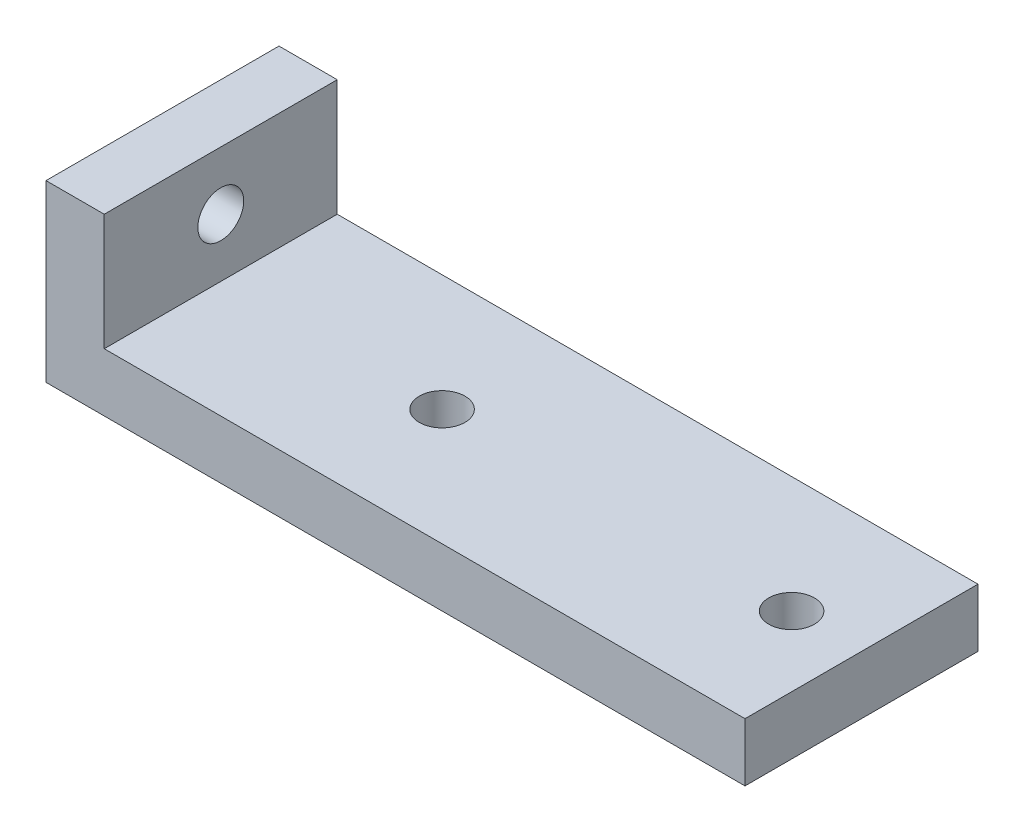
SolidWorks part; units mm, degrees
ref_plane "Front Plane" through (0, 0, 0) normal (0, 0, 1) x (1, 0, 0)
ref_plane "Top Plane" through (0, 0, 0) normal (0, 1, 0) x (1, 0, 0)
ref_plane "Right Plane" through (0, 0, 0) normal (1, 0, 0) x (0, 0, -1)
sketch "Sketch1" plane through (0, 0, 0) normal (0, 1, 0) x (1, 0, 0)
  line L1 (0, 0) -> (-76.2, 0)
  line L2 (0, 0) -> (0, 25.4)
  line L3 (0, 25.4) -> (-76.2, 25.4)
  line L4 (-76.2, 0) -> (-76.2, 25.4)
  dimension "D1" = 25.4
  dimension "D2" = 76.2
extrude "Boss-Extrude1" add sketch "Sketch1" along normal blind 19.05
sketch "Sketch2" plane through (0, 0, 0) normal (0, 0, 1) x (1, 0, 0)
  line L0 (-76.2, 19.05) -> (-76.2, 0) construction
  line L1 (0, 19.05) -> (-69.85, 19.05)
  line L2 (0, 19.05) -> (0, 6.35)
  line L3 (0, 6.35) -> (-69.85, 6.35)
  line L4 (-69.85, 19.05) -> (-69.85, 6.35)
  line L5 (-76.2, 0) -> (0, 0) construction
  dimension "D1" = 6.35
  dimension "D2" = 6.35
extrude "Cut-Extrude1" cut sketch "Sketch2" against normal through all
sketch "Sketch3" plane through (-76.2, 0, 0) normal (-1, 0, 0) x (0, 0, 1)
  line L0 (-12.7, 19.05) -> (-12.7, 0) construction
  line L1 (-25.4, 19.05) -> (0, 19.05) construction
  line L2 (-25.4, 0) -> (0, 0) construction
  point P6 (-12.7, 12.7)
  dimension "D1" = 6.35
hole_wizard "M6x1.0 Tapped Hole1" positions "Sketch5" profile "Sketch4" tap size "M6x1.0" standard "ANSI Metric" end condition through all
sketch "Sketch5" plane through (-76.2, 0, 0) normal (-1, 0, 0) x (0, 0, 1)
  point P0 (-12.7, 12.7)
sketch "Sketch4" plane through (-76.2, 12.7, -12.7) normal (0, 1, 0) x (0, 0, 1)
  line L0 (0, 0) -> (0, 76.2)
  line L1 (0, 76.2) -> (2.5, 76.2)
  line L2 (2.5, 76.2) -> (2.5, 0)
  line L5 (2.5, 0) -> (0, 0)
  line L11 (0, -6.35) -> (0, 107.95) construction
  dimension "Thru Tap Drill Dia." = 5
  dimension "Thru Tap Drill Depth" = 76.2
cosmetic thread "Hole Thread1" parameters "D2"=6
sketch "Sketch6" plane through (0, 6.35, 0) normal (0, 1, 0) x (1, 0, 0)
  line L0 (-76.2, 25.4) -> (-76.2, 0) construction
  line L1 (-76.2, 25.4) -> (-76.2, 0) construction
  line L2 (-76.2, 12.7) -> (0, 12.7) construction
  line L3 (0, 25.4) -> (0, 0) construction
  point P6 (-45.72, 12.7)
  point P7 (-7.62, 12.7)
  dimension "D1" = 30.48
  dimension "D2" = 38.1
hole_wizard "#9 (0.196) Diameter Hole1" positions "Sketch8" profile "Sketch7" hole size "#9" standard "ANSI Inch" end condition through all
sketch "Sketch8" plane through (0, 6.35, 0) normal (0, 1, 0) x (1, 0, 0)
  point P0 (-45.72, 12.7)
  point P3 (-7.62, 12.7)
sketch "Sketch7" plane through (-45.72, 6.35, -12.7) normal (1, 0, 0) x (0, 0, 1)
  line L0 (0, 0) -> (0, 6.35)
  line L1 (0, 6.35) -> (2.4892, 6.35)
  line L2 (2.4892, 6.35) -> (2.4892, 0)
  line L5 (2.4892, 0) -> (0, 0)
  line L11 (0, -6.35) -> (0, 107.95) construction
  dimension "Thru Hole Dia." = 4.9784
  dimension "Thru Hole Depth" = 6.35
